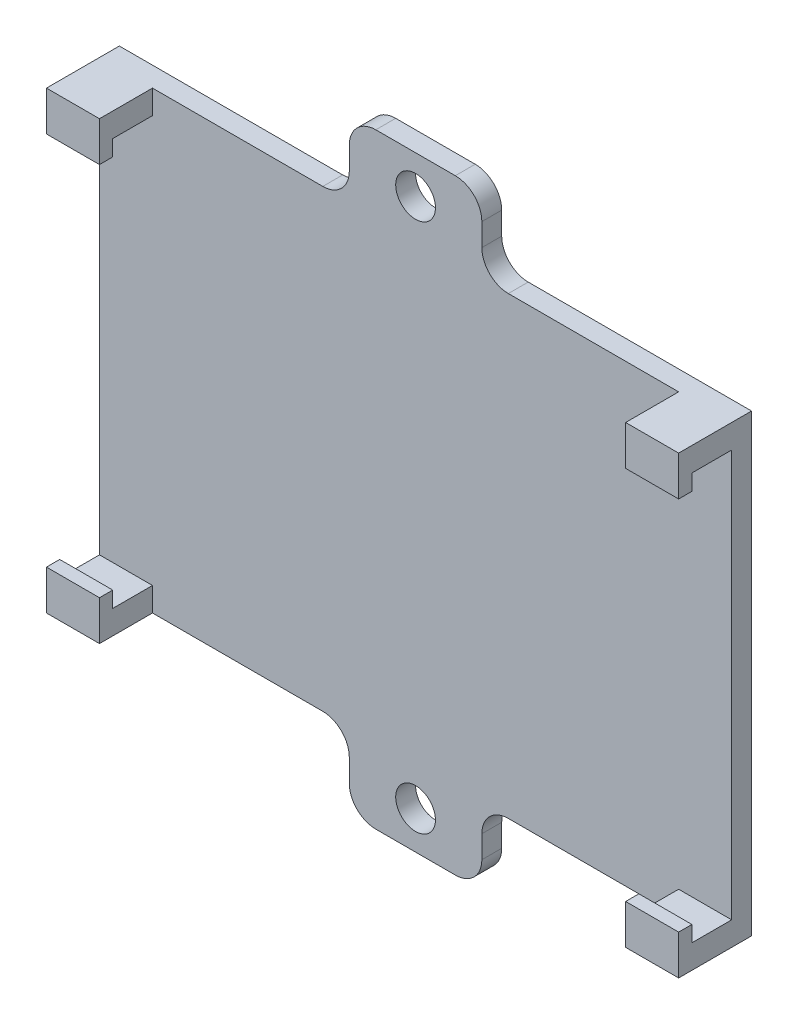
SolidWorks part; units mm, degrees
ref_plane "Front" through (0, 0, 0) normal (0, 0, 1) x (1, 0, 0)
ref_plane "Top" through (0, 0, 0) normal (0, 1, 0) x (1, 0, 0)
ref_plane "Right" through (0, 0, 0) normal (1, 0, 0) x (0, 0, -1)
sketch "Sketch1" plane through (0, 0, 0) normal (0, 1, 0) x (1, 0, 0)
  line L1 (0, 0) -> (47.7, 0)
  line L2 (0, 0) -> (0, 45.7)
  line L3 (0, 45.7) -> (47.7, 45.7)
  line L4 (47.7, 0) -> (47.7, 45.7)
  dimension "D1" = 47.7
  dimension "D2" = 45.7
extrude "Boss-Extrude1" add sketch "Sketch1" along normal blind 1.5
sketch "Sketch2" plane through (0, 1.5, 0) normal (0, 1, 0) x (1, 0, 0)
  line L0 (0, 45.7) -> (0, 0) construction
  line L1 (0, 37) -> (47.7, 37)
  line L2 (0, 37) -> (0, 40)
  line L3 (0, 40) -> (47.7, 40)
  line L4 (47.7, 37) -> (47.7, 40)
  line L5 (47.7, 0) -> (47.7, 45.7) construction
  line L7 (0, 8.7) -> (47.7, 8.7)
  line L8 (0, 8.7) -> (0, 5.7)
  line L9 (0, 5.7) -> (47.7, 5.7)
  line L10 (47.7, 8.7) -> (47.7, 5.7)
  line L11 (23.85, 8.7) -> (23.85, 37) construction
  point P14 (0, 22.85)
  point P15 (23.85, 22.85)
  dimension "D2" = 3
  dimension "D3" = 3
  dimension "D1" = 28.3
extrude "Boss-Extrude2" add sketch "Sketch2" along normal blind 4
sketch "Sketch3" plane through (0, 0, -37) normal (0, 0, 1) x (1, 0, 0)
  line L0 (47.7, 5.5) -> (47.7, 1.5) construction
  line L1 (0, 1.5) -> (47.7, 1.5)
  line L2 (0, 1.5) -> (0, 4.5)
  line L3 (0, 4.5) -> (47.7, 4.5)
  line L4 (47.7, 1.5) -> (47.7, 4.5)
  dimension "D1" = 3
extrude "Cut-Extrude1" cut sketch "Sketch3" against normal blind 1.2
sketch "Sketch4" plane through (0, 0, -8.7) normal (0, 0, -1) x (-1, 0, 0)
  line L0 (0, 5.5) -> (0, 1.5) construction
  line L1 (-47.7, 1.5) -> (0, 1.5)
  line L2 (-47.7, 1.5) -> (-47.7, 4.5)
  line L3 (-47.7, 4.5) -> (0, 4.5)
  line L4 (0, 1.5) -> (0, 4.5)
  dimension "D1" = 3
extrude "Cut-Extrude2" cut sketch "Sketch4" against normal blind 1.2
sketch "Sketch5" plane through (0, 1.5, 0) normal (0, 1, 0) x (1, 0, 0)
  line L0 (0, 45.7) -> (0, 40) construction
  line L1 (47.7, 45.7) -> (0, 45.7) construction
  line L2 (0, 5.7) -> (0, 0) construction
  circle A0 centre (23.85, 42.85) radius 1.5
  circle A1 centre (23.85, 2.85) radius 1.5
  point P6 (0, 42.85)
  point P9 (23.85, 45.7)
  point P12 (0, 2.85)
  dimension "D1" = 3
  dimension "D2" = 3
extrude "Cut-Extrude3" cut sketch "Sketch5" against normal through all
sketch "Sketch6" plane through (0, 0, 0) normal (0, -1, 0) x (1, 0, 0)
  line L0 (23.85, -42.85) -> (23.85, -5.7)
  line L1 (0, -5.7) -> (47.7, -5.7) construction
sketch "Sketch7" plane through (0, 0, 0) normal (0, 1, 0) x (1, 0, 0)
  line L1 (0, 5.7) -> (47.7, 5.7)
  line L2 (0, 5.7) -> (0, 0)
  line L3 (0, 0) -> (47.7, 0)
  line L4 (47.7, 5.7) -> (47.7, 0)
extrude "Cut-Extrude4" [suppressed] cut sketch "Sketch7" along normal through all
sketch "Sketch8" plane through (0, 0, -5.7) normal (0, 0, 1) x (1, 0, 0)
  line L0 (0, 5.5) -> (47.7, 5.5) construction
  line L1 (4, 5.5) -> (43.7, 5.5)
  line L2 (4, 5.5) -> (4, 1.5)
  line L3 (4, 1.5) -> (43.7, 1.5)
  line L4 (43.7, 5.5) -> (43.7, 1.5)
  line L5 (0, 1.5) -> (47.7, 1.5) construction
  line L6 (0, 1.5) -> (4, 1.5) construction
  line L16 (0, 5.5) -> (0, 1.5) construction
  point P8 (23.85, 5.5)
  point P9 (23.85, 5.5)
  dimension "D1" = 4
extrude "Cut-Extrude5" cut sketch "Sketch8" against normal through all
sketch "Sketch9" plane through (0, 1.5, 0) normal (0, 1, 0) x (1, 0, 0)
  line L0 (4, 40) -> (0, 40) construction
  line L1 (0, 45.7) -> (18.85, 45.7)
  line L2 (0, 45.7) -> (0, 40)
  line L3 (0, 40) -> (18.85, 40)
  line L4 (18.85, 45.7) -> (18.85, 40)
  line L5 (23.85, 45.7) -> (23.85, 5.7) construction
  line L6 (47.7, 45.7) -> (0, 45.7) construction
  line L8 (28.85, 45.7) -> (28.85, 40)
  line L9 (47.7, 40) -> (28.85, 40)
  line L10 (47.7, 45.7) -> (47.7, 40)
  line L11 (47.7, 45.7) -> (28.85, 45.7)
  line L12 (0, 22.85) -> (47.7, 22.85) construction
  line L13 (0, 38.2) -> (0, 7.5) construction
  line L14 (47.7, 7.5) -> (47.7, 38.2) construction
  line L15 (47.7, 0) -> (28.85, 0)
  line L16 (47.7, 0) -> (47.7, 5.7)
  line L17 (47.7, 5.7) -> (28.85, 5.7)
  line L18 (28.85, 0) -> (28.85, 5.7)
  line L19 (18.85, 0) -> (18.85, 5.7)
  line L20 (0, 5.7) -> (18.85, 5.7)
  line L21 (0, 0) -> (0, 5.7)
  line L22 (0, 0) -> (18.85, 0)
  dimension "D1" = 5
extrude "Cut-Extrude6" cut sketch "Sketch9" against normal through all
fillet "Fillet1" radius 2 8 edges at (18.85, 0.75, -40) (18.85, 0.75, -45.7) (28.85, 0.75, -45.7) (28.85, 0.75, -40) (28.85, 0.75, -5.7) (28.85, 0.75, 0) (18.85, 0.75, 0) (18.85, 0.75, -5.7)
move or copy body "Body-Move/Copy1" bodies to move or copy 109 copy no rotation origin (0, 2.75, -20.7) rotation axis (1, 0, 0) rotation angle 90
equation "\"Board Length\"= 30.7'The dimension of the board parallel with the clips"
equation "\"Board Width\" = 47.7'The dimension of the board perpendicular to the clips"
equation "\"D1@Sketch1\"=\"Board Width\""
equation "\"Board Slot Length\"= \"Board Length\" - 2 * \"Overhang Cut\""
equation "\"Overhang Cut\"= 1.2"
equation "\"D1@Cut-Extrude1\"=\"Overhang Cut\""
equation "\"D1@Sketch2\"=\"Board Slot Length\""
equation "\"Mount Length\"= \"Board Length\" + 7.5 * 2"
equation "\"D2@Sketch1\"=\"Mount Length\""
